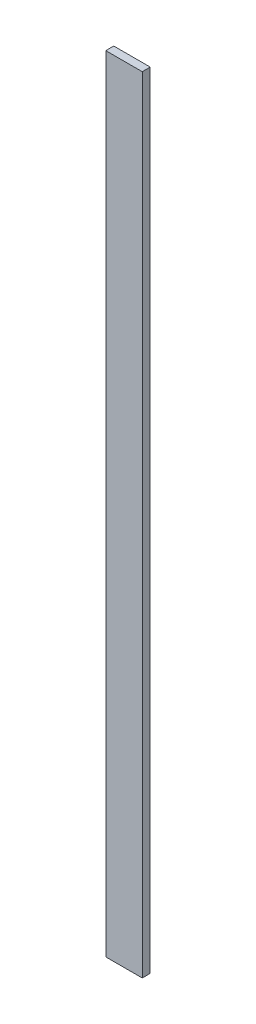
SolidWorks part; units mm, degrees
ref_plane "Front Plane" through (0, 0, 0) normal (0, 0, 1) x (1, 0, 0)
ref_plane "Top Plane" through (0, 0, 0) normal (0, 1, 0) x (1, 0, 0)
ref_plane "Right Plane" through (0, 0, 0) normal (1, 0, 0) x (0, 0, -1)
sketch "Sketch1" plane through (0, 0, 0) normal (0, 0, 1) x (1, 0, 0)
  line L1 (-41.6719, -896.1438) -> (41.6719, -896.1438)
  line L2 (-41.6719, -896.1438) -> (-41.6719, 896.1437)
  line L3 (-41.6719, 896.1437) -> (41.6719, 896.1437)
  line L4 (41.6719, -896.1438) -> (41.6719, 896.1437)
  line L5 (-41.6719, -896.1438) -> (41.6719, 896.1437) construction
  line L6 (-41.6719, 896.1437) -> (41.6719, -896.1438) construction
  point P0 (0, 0)
  dimension "D1" = 83.3438
  dimension "D2" = 1792.2875
extrude "Boss-Extrude1" add sketch "Sketch1" along normal blind 18.2562
